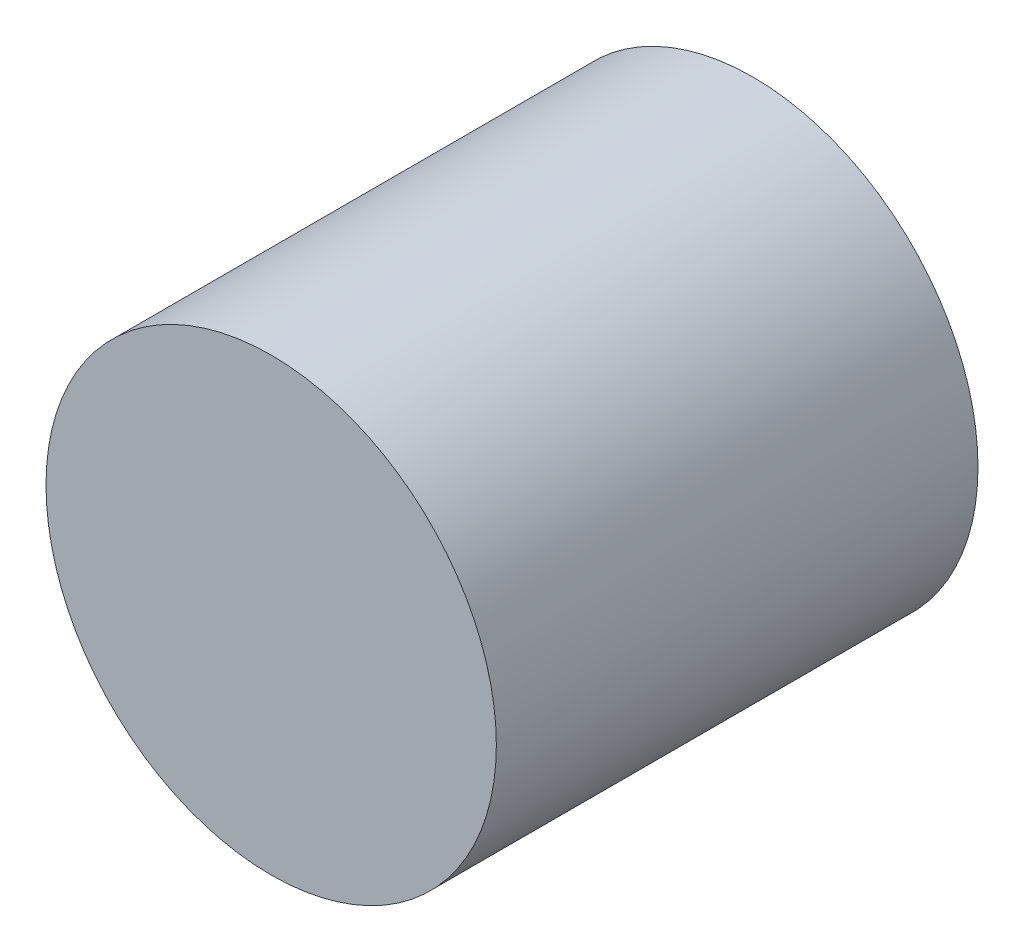
SolidWorks part; units mm, degrees
ref_plane "Front Plane" through (0, 0, 0) normal (0, 0, 1) x (1, 0, 0)
ref_plane "Top Plane" through (0, 0, 0) normal (0, 1, 0) x (1, 0, 0)
ref_plane "Right Plane" through (0, 0, 0) normal (1, 0, 0) x (0, 0, -1)
sketch "Sketch1" plane through (0, 0, 0) normal (0, 0, 1) x (1, 0, 0)
  circle A0 centre (0, 0) radius 23.749
  dimension "D1" = 47.498
extrude "Boss-Extrude1" add sketch "Sketch1" along normal blind 50.8
